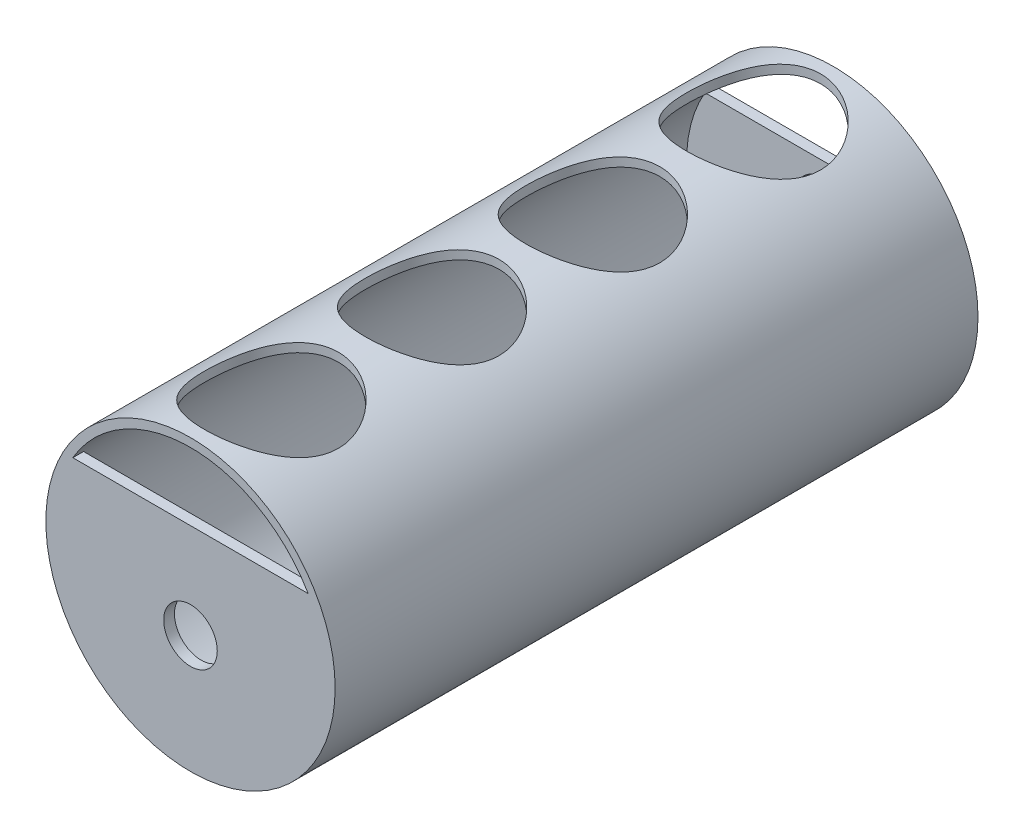
SolidWorks part; units mm, degrees
ref_plane "Front Plane" through (0, 0, 0) normal (0, 0, 1) x (1, 0, 0)
ref_plane "Top Plane" through (0, 0, 0) normal (0, 1, 0) x (1, 0, 0)
ref_plane "Right Plane" through (0, 0, 0) normal (1, 0, 0) x (0, 0, -1)
sketch "Sketch1" plane through (0, 0, 0) normal (0, 0, 1) x (1, 0, 0)
  line L4 (-20.3241, 15.2346) -> (20.3241, -15.2346) construction
  line L5 (-20.3241, -15.2346) -> (20.3241, 15.2346) construction
  circle A0 centre (0, 0) radius 25.4
  point P4 (0, 0)
  dimension "D2" = 50.8
extrude "Extrude-Thin1" add sketch "Sketch1" along normal blind 120 thin
sketch "Sketch2" plane through (0, 0, 120) normal (0, 0, 1) x (1, 0, 0)
  line L0 (-21.9644, 12.7563) -> (21.9644, 12.7563)
  circle A0 centre (0, 0) radius 25.4 construction
  circle A1 centre (0, 0) radius 25.4
  circle M2 centre (0, 0) radius 25.4
extrude "Boss-Extrude1" add sketch "Sketch2" against normal blind 2 contours L0 M2
sketch "Sketch3" plane through (0, 0, 0) normal (0, 0, -1) x (-1, 0, 0)
  line L0 (21.9644, 12.7563) -> (-21.9644, 12.7563) construction
  line L1 (21.9644, 12.7563) -> (-21.9644, 12.7563)
  circle A0 centre (0, 0) radius 25.4 construction
  circle A1 centre (0, 0) radius 27
  circle A2 centre (0, 0) radius 27
  circle A3 centre (0, 0) radius 25.4
  circle M3 centre (0, 0) radius 25.4
  dimension "D1" = 0
extrude "Boss-Extrude2" add sketch "Sketch3" against normal blind 2 contours L1 M3
sketch "Sketch4" plane through (0, 0, 0) normal (0, 1, 0) x (1, 0, 0)
  line L0 (0, 0) -> (0, -119.9943) construction
  circle A0 centre (0, -14.8997) radius 12.5
  circle A1 centre (0, -44.8997) radius 12.5
  circle A2 centre (0, -74.8997) radius 12.5
  circle A3 centre (0, -104.8997) radius 12.5
  dimension "D2" = 25
  dimension "D1" = 4
extrude "Cut-Extrude2" cut sketch "Sketch4" along normal blind 31
sketch "Sketch5" plane through (0, 0, 0) normal (0, 0, -1) x (-1, 0, 0)
  circle A0 centre (0, 5) radius 5
  dimension "D1" = 10
  dimension "D2" = 5
extrude "Cut-Extrude3" cut sketch "Sketch5" against normal blind 18
sketch "Sketch6" plane through (0, 0, 120) normal (0, 0, 1) x (1, 0, 0)
  circle A0 centre (0, -5) radius 5
  dimension "D1" = 10
  dimension "D2" = 5
extrude "Cut-Extrude4" cut sketch "Sketch6" against normal blind 18
